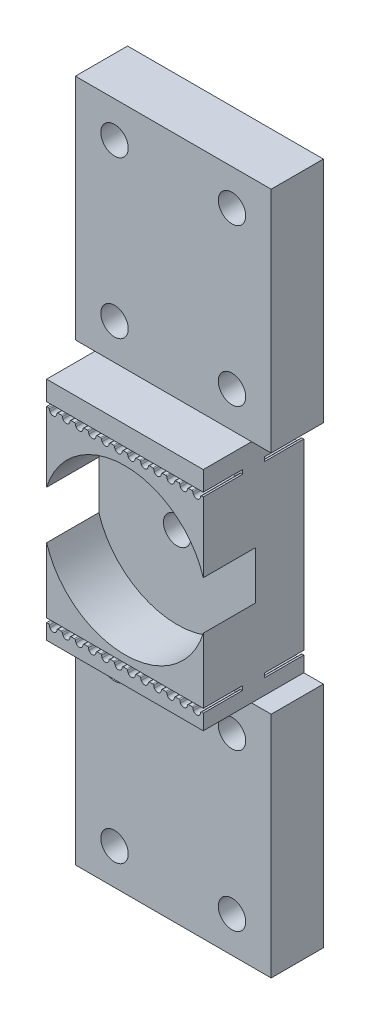
SolidWorks part; units mm, degrees
ref_plane "Front Plane" through (0, 0, 0) normal (0, 0, 1) x (1, 0, 0)
ref_plane "Top Plane" through (0, 0, 0) normal (0, 1, 0) x (1, 0, 0)
ref_plane "Right Plane" through (0, 0, 0) normal (1, 0, 0) x (0, 0, -1)
sketch "Sketch1" plane through (0, 0, 0) normal (0, 0, 1) x (1, 0, 0)
  line L0 (-2, 0.376) -> (2, 0.376) construction
  line L1 (-0.2598, -0.254) -> (0, -0.254)
  line L2 (1, -1.004) -> (1, 0.4576) construction
  line L3 (2, -0.254) -> (1.7402, -0.254)
  line L4 (-2.1801, 0) -> (2.1541, 0) construction
  line L5 (1.4, -0.5041) -> (1.4, -0.1557) construction
  line L6 (0, 0.4576) -> (0, -1.2142) construction
  line L7 (-2, -0.254) -> (-1.7402, -0.254)
  line L8 (-2.1801, -1.004) -> (2.1541, -1.004) construction
  line L9 (-2, 0.376) -> (-2, -0.254)
  line L10 (10, -0.254) -> (10, -3.254)
  line L11 (-1, -1.004) -> (-1, 0.376) construction
  line L12 (0, -0.254) -> (0.2598, -0.254)
  line L13 (4, -0.254) -> (3.7402, -0.254)
  line L14 (2, -0.254) -> (2.2598, -0.254)
  line L15 (6, -0.254) -> (5.7402, -0.254)
  line L16 (4, -0.254) -> (4.2598, -0.254)
  line L17 (8, -0.254) -> (7.7402, -0.254)
  line L18 (6, -0.254) -> (6.2598, -0.254)
  line L19 (10, -0.254) -> (9.7402, -0.254)
  line L20 (8, -0.254) -> (8.2598, -0.254)
  line L21 (-0.2598, -28.934) -> (0, -28.934)
  line L22 (-2, 3.376) -> (-5, 3.376)
  line L23 (-2, 0.376) -> (10, 0.376)
  line L24 (-5, 3.376) -> (-5, -3.254)
  line L25 (-2, 3.376) -> (10, 3.376)
  line L26 (10, 0.376) -> (10, 3.376)
  line L27 (2, -28.934) -> (1.7402, -28.934)
  line L28 (-2, -28.934) -> (-1.7402, -28.934)
  line L29 (-2, -28.304) -> (-2, -28.934)
  line L30 (10, -3.254) -> (10, -28.304)
  line L31 (10, -31.284) -> (-5, -31.284)
  line L32 (-5, -3.254) -> (-5, -31.284)
  line L33 (0, -28.934) -> (0.2598, -28.934)
  line L34 (4, -28.934) -> (3.7402, -28.934)
  line L35 (2, -28.934) -> (2.2598, -28.934)
  line L36 (6, -28.934) -> (5.7402, -28.934)
  line L37 (4, -28.934) -> (4.2598, -28.934)
  line L38 (8, -28.934) -> (7.7402, -28.934)
  line L39 (6, -28.934) -> (6.2598, -28.934)
  line L40 (10, -28.934) -> (9.7402, -28.934)
  line L41 (8, -28.934) -> (8.2598, -28.934)
  line L42 (-2, -28.304) -> (10, -28.304)
  line L43 (-2, -28.304) -> (2, -28.304) construction
  line L44 (1, -29.684) -> (1, -28.2224) construction
  line L45 (-2.1801, -28.68) -> (2.1541, -28.68) construction
  line L46 (1.4, -29.1841) -> (1.4, -28.8357) construction
  line L47 (0, -28.2224) -> (0, -29.8942) construction
  line L48 (-2.1801, -29.684) -> (2.1541, -29.684) construction
  line L49 (-1, -29.684) -> (-1, -28.304) construction
  line L50 (10, -28.934) -> (10, -31.284)
  arc A0 (0.5011, -0.6922) -> (1.4989, -0.6922) centre (1, -0.449) ccw
  arc A1 (0.4085, -0.3844) -> (0.5011, -0.6922) centre (1.4, -0.254) ccw
  arc A2 (0.4085, -0.3844) -> (0.2598, -0.254) centre (0.2598, -0.404) ccw
  arc A3 (1.5915, -0.3844) -> (1.7402, -0.254) centre (1.7402, -0.404) cw
  arc A4 (1.5915, -0.3844) -> (1.4989, -0.6922) centre (0.6, -0.254) cw
  arc A5 (-0.4085, -0.3844) -> (-0.2598, -0.254) centre (-0.2598, -0.404) cw
  arc A6 (-0.4085, -0.3844) -> (-0.5011, -0.6922) centre (-1.4, -0.254) cw
  arc A7 (-1.5915, -0.3844) -> (-1.7402, -0.254) centre (-1.7402, -0.404) ccw
  arc A8 (-1.5915, -0.3844) -> (-1.4989, -0.6922) centre (-0.6, -0.254) ccw
  arc A9 (-0.5011, -0.6922) -> (-1.4989, -0.6922) centre (-1, -0.449) cw
  arc A10 (3.5915, -0.3844) -> (3.7402, -0.254) centre (3.7402, -0.404) cw
  arc A11 (3.5915, -0.3844) -> (3.4989, -0.6922) centre (2.6, -0.254) cw
  arc A12 (2.5011, -0.6922) -> (3.4989, -0.6922) centre (3, -0.449) ccw
  arc A13 (2.4085, -0.3844) -> (2.5011, -0.6922) centre (3.4, -0.254) ccw
  arc A14 (2.4085, -0.3844) -> (2.2598, -0.254) centre (2.2598, -0.404) ccw
  arc A15 (5.5915, -0.3844) -> (5.7402, -0.254) centre (5.7402, -0.404) cw
  arc A16 (5.5915, -0.3844) -> (5.4989, -0.6922) centre (4.6, -0.254) cw
  arc A17 (4.5011, -0.6922) -> (5.4989, -0.6922) centre (5, -0.449) ccw
  arc A18 (4.4085, -0.3844) -> (4.5011, -0.6922) centre (5.4, -0.254) ccw
  arc A19 (4.4085, -0.3844) -> (4.2598, -0.254) centre (4.2598, -0.404) ccw
  arc A20 (7.5915, -0.3844) -> (7.7402, -0.254) centre (7.7402, -0.404) cw
  arc A21 (7.5915, -0.3844) -> (7.4989, -0.6922) centre (6.6, -0.254) cw
  arc A22 (6.5011, -0.6922) -> (7.4989, -0.6922) centre (7, -0.449) ccw
  arc A23 (6.4085, -0.3844) -> (6.5011, -0.6922) centre (7.4, -0.254) ccw
  arc A24 (6.4085, -0.3844) -> (6.2598, -0.254) centre (6.2598, -0.404) ccw
  arc A25 (9.5915, -0.3844) -> (9.7402, -0.254) centre (9.7402, -0.404) cw
  arc A26 (9.5915, -0.3844) -> (9.4989, -0.6922) centre (8.6, -0.254) cw
  arc A27 (8.5011, -0.6922) -> (9.4989, -0.6922) centre (9, -0.449) ccw
  arc A28 (8.4085, -0.3844) -> (8.5011, -0.6922) centre (9.4, -0.254) ccw
  arc A29 (8.4085, -0.3844) -> (8.2598, -0.254) centre (8.2598, -0.404) ccw
  arc A30 (0.5011, -29.3722) -> (1.4989, -29.3722) centre (1, -29.129) ccw
  arc A31 (0.4085, -29.0644) -> (0.5011, -29.3722) centre (1.4, -28.934) ccw
  arc A32 (0.4085, -29.0644) -> (0.2598, -28.934) centre (0.2598, -29.084) ccw
  arc A33 (1.5915, -29.0644) -> (1.7402, -28.934) centre (1.7402, -29.084) cw
  arc A34 (1.5915, -29.0644) -> (1.4989, -29.3722) centre (0.6, -28.934) cw
  arc A35 (-0.4085, -29.0644) -> (-0.2598, -28.934) centre (-0.2598, -29.084) cw
  arc A36 (-0.4085, -29.0644) -> (-0.5011, -29.3722) centre (-1.4, -28.934) cw
  arc A37 (-1.5915, -29.0644) -> (-1.7402, -28.934) centre (-1.7402, -29.084) ccw
  arc A38 (-1.5915, -29.0644) -> (-1.4989, -29.3722) centre (-0.6, -28.934) ccw
  arc A39 (-0.5011, -29.3722) -> (-1.4989, -29.3722) centre (-1, -29.129) cw
  arc A40 (3.5915, -29.0644) -> (3.7402, -28.934) centre (3.7402, -29.084) cw
  arc A41 (3.5915, -29.0644) -> (3.4989, -29.3722) centre (2.6, -28.934) cw
  arc A42 (2.5011, -29.3722) -> (3.4989, -29.3722) centre (3, -29.129) ccw
  arc A43 (2.4085, -29.0644) -> (2.5011, -29.3722) centre (3.4, -28.934) ccw
  arc A44 (2.4085, -29.0644) -> (2.2598, -28.934) centre (2.2598, -29.084) ccw
  arc A45 (5.5915, -29.0644) -> (5.7402, -28.934) centre (5.7402, -29.084) cw
  arc A46 (5.5915, -29.0644) -> (5.4989, -29.3722) centre (4.6, -28.934) cw
  arc A47 (4.5011, -29.3722) -> (5.4989, -29.3722) centre (5, -29.129) ccw
  arc A48 (4.4085, -29.0644) -> (4.5011, -29.3722) centre (5.4, -28.934) ccw
  arc A49 (4.4085, -29.0644) -> (4.2598, -28.934) centre (4.2598, -29.084) ccw
  arc A50 (7.5915, -29.0644) -> (7.7402, -28.934) centre (7.7402, -29.084) cw
  arc A51 (7.5915, -29.0644) -> (7.4989, -29.3722) centre (6.6, -28.934) cw
  arc A52 (6.5011, -29.3722) -> (7.4989, -29.3722) centre (7, -29.129) ccw
  arc A53 (6.4085, -29.0644) -> (6.5011, -29.3722) centre (7.4, -28.934) ccw
  arc A54 (6.4085, -29.0644) -> (6.2598, -28.934) centre (6.2598, -29.084) ccw
  arc A55 (9.5915, -29.0644) -> (9.7402, -28.934) centre (9.7402, -29.084) cw
  arc A56 (9.5915, -29.0644) -> (9.4989, -29.3722) centre (8.6, -28.934) cw
  arc A57 (8.5011, -29.3722) -> (9.4989, -29.3722) centre (9, -29.129) ccw
  arc A58 (8.4085, -29.0644) -> (8.5011, -29.3722) centre (9.4, -28.934) ccw
  arc A59 (8.4085, -29.0644) -> (8.2598, -28.934) centre (8.2598, -29.084) ccw
  point P24 (0, -0.254)
  point P123 (0, -28.934)
  dimension "D4" = 0.555
  dimension "D5" = 1
  dimension "D6" = 0.15
  dimension "D1" = 0.254
  dimension "D2" = 0.4
  dimension "D3" = 1
  dimension "D7" = 1.38
  dimension "D8" = 0.75
  dimension "D9" = 0.5196
  dimension "D10" = 5
  dimension "D11" = 31.66
  dimension "D12" = 3
  dimension "D13" = 3
  dimension "D14" = 30.28
  dimension "D15" = 2
extrude "Boss-Extrude1" add sketch "Sketch1" along normal blind 6
sketch "Sketch2" plane through (0, 0, 0) normal (0, 0, -1) x (-1, 0, 0)
  line L1 (-10, 3.376) -> (5, 3.376)
  line L2 (-10, 3.376) -> (-10, -31.284)
  line L3 (-10, -31.284) -> (5, -31.284)
  line L4 (5, 3.376) -> (5, -31.284)
extrude "Boss-Extrude2" add sketch "Sketch2" along normal blind 1.7
sketch "Sketch3" plane through (0, 0, 6) normal (0, 0, 1) x (1, 0, 0)
  line L0 (-2, 0.376) -> (-2, 3.376) construction
  line L1 (10, 3.376) -> (-5, 3.376) construction
  line L3 (-2, 3.376) -> (-5, 3.376)
  line L4 (-2, 3.376) -> (-2, -31.284)
  line L5 (-2, -31.284) -> (-5, -31.284)
  line L6 (-5, 3.376) -> (-5, -31.284)
extrude "Cut-Extrude1" cut sketch "Sketch3" against normal up to surface (7.7 mm away) up to face at (2.5, -13.954, -1.7)
mirror "Mirror1" about plane through (-2, 3.376, -36.4896) normal (1, 0, 0) of bodies 107
mirror "Mirror2" about plane through (0, 0, -1.7) normal (0, 0, -1) of bodies 108
sketch "Sketch4" plane through (0, 0, 6) normal (0, 0, 1) x (1, 0, 0)
  line L0 (7, -1.004) -> (7, -28.304) construction
  line L3 (-14, -28.304) -> (10, -28.304) construction
  line L4 (10, -14.654) -> (-14, -14.654) construction
  line L7 (10, -28.304) -> (10, -0.254) construction
  line L8 (-14, -28.304) -> (-14, -0.254) construction
  arc A1 (6.5011, -0.6922) -> (7.4989, -0.6922) centre (7, -0.449) ccw construction
  circle A2 centre (-2, -14.654) radius 12.55
  point P14 (7, -14.654)
  dimension "D1" = 25.1
extrude "Cut-Extrude2" cut sketch "Sketch4" against normal blind 8
sketch "Sketch6" plane through (0, 0, -2) normal (0, 0, 1) x (1, 0, 0)
  line L0 (10, -10.9794) -> (10, -18.3286) construction
  line L1 (10, -18.3286) -> (10, -14.654) construction
  line L2 (10, -14.654) -> (-14, -14.654) construction
  line L3 (-14, -10.9794) -> (-14, -18.3286) construction
  circle A0 centre (-2, -14.654) radius 2.1
  dimension "D1" = 4.2
extrude "Cut-Extrude3" cut sketch "Sketch6" against normal up to next
sketch "Sketch7" plane through (0, 0, -9.4) normal (0, 0, -1) x (-1, 0, 0)
  line L0 (14, 3.376) -> (17, 3.376)
  line L1 (17, 3.376) -> (17, 38.376)
  line L2 (17, 38.376) -> (-13, 38.376)
  line L3 (-13, 38.376) -> (-13, 3.376)
  line L4 (-13, 3.376) -> (-10, 3.376)
  line L5 (-10, 3.376) -> (14, 3.376)
  line L6 (2, 38.376) -> (2, 3.376) construction
  line L7 (2, 20.876) -> (11, 20.876) construction
  line L8 (11, 20.876) -> (11, 32.876) construction
  line L9 (14, 3.376) -> (14, -31.284) construction
  line L10 (14, -13.954) -> (-14.6026, -13.954) construction
  line L11 (11, -48.784) -> (11, -60.784) construction
  line L12 (2, -48.784) -> (11, -48.784) construction
  line L13 (2, -66.284) -> (2, -31.284) construction
  line L14 (-10, -31.284) -> (14, -31.284)
  line L15 (-13, -31.284) -> (-10, -31.284)
  line L16 (-13, -66.284) -> (-13, -31.284)
  line L17 (17, -66.284) -> (-13, -66.284)
  line L18 (17, -31.284) -> (17, -66.284)
  line L19 (14, -31.284) -> (17, -31.284)
  circle A0 centre (11, 32.876) radius 2.1
  circle A1 centre (11, 8.876) radius 2.1
  circle A2 centre (-7, 8.876) radius 2.1
  circle A3 centre (-7, 32.876) radius 2.1
  circle A4 centre (-7, -60.784) radius 2.1
  circle A5 centre (-7, -36.784) radius 2.1
  circle A6 centre (11, -36.784) radius 2.1
  circle A7 centre (11, -60.784) radius 2.1
  dimension "D5" = 4.2
  dimension "D1" = 30
  dimension "D2" = 35
  dimension "D3" = 9
  dimension "D4" = 12
extrude "Boss-Extrude3" add sketch "Sketch7" against normal blind 8
